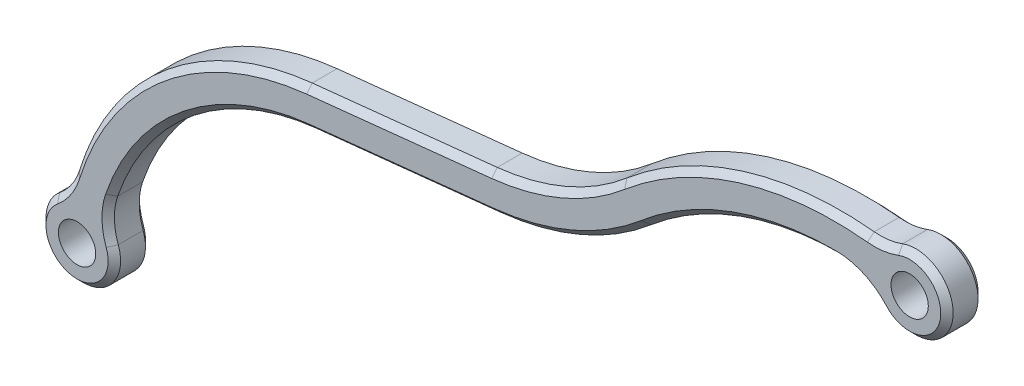
SolidWorks part; units mm, degrees
ref_plane "Спереди" through (0, 0, 0) normal (0, 0, 1) x (1, 0, 0)
ref_plane "Сверху" through (0, 0, 0) normal (0, 1, 0) x (1, 0, 0)
ref_plane "Справа" through (0, 0, 0) normal (1, 0, 0) x (0, 0, -1)
other "Configuration Table"
sketch "Sketch1" plane through (0, 0, 0) normal (0, 0, 1) x (1, 0, 0)
  line L0 (-54.4883, 1.7083) -> (-63.9363, 0.7152) construction
  line L1 (-54.4883, 1.7083) -> (-63.9363, 0.7152) construction
  line L2 (-65.383, -1.297) -> (-50.4992, 0.2674)
  circle A0 centre (-83.9505, -19.9121) radius 1.5 construction
  circle A1 centre (-83.9505, -19.9121) radius 1.5
  circle A2 centre (-17, 9.9282) radius 1.5 construction
  circle A3 centre (-17, 9.9282) radius 1.5
  circle A4 centre (-83.9505, -19.9121) radius 3
  circle A5 centre (-17, 9.9282) radius 3
  arc A6 (-12.8452, 4.492) -> (-12.8452, 1.508) centre (-13, 3) ccw construction
  arc A7 (-12.8452, 4.492) -> (-12.8452, 1.508) centre (-13, 3) ccw construction
  arc A9 (-83.3396, -17.8158) -> (-65.383, -1.297) centre (-63.2448, -21.6405) cw
  arc A10 (-50.4992, 0.2674) -> (-39.2623, 5.0886) centre (-52.6577, 20.804) ccw
  arc A11 (-39.2623, 5.0886) -> (-19.139, 10.7644) centre (-23.0284, -13.9569) cw
  dimension "D1" = 6
  dimension "D2" = 6
extrude "Boss-Extrude1" add sketch "Sketch1" along normal blind 3
sketch "Sketch2" plane through (0, 0, 0) normal (0, 0, 1) x (1, 0, 0)
  line L0 (-65.383, -1.297) -> (-50.4992, 0.2674) construction
  line L1 (-65.383, -1.297) -> (-50.4992, 0.2674)
  arc A0 (-19.139, 10.7644) -> (-39.2623, 5.0886) centre (-23.0284, -13.9569) ccw construction
  arc A1 (-50.4992, 0.2674) -> (-39.2623, 5.0886) centre (-52.6577, 20.804) ccw construction
  arc A2 (-65.383, -1.297) -> (-83.3396, -17.8158) centre (-63.2448, -21.6405) ccw construction
  arc A3 (-18.8959, 10.7249) -> (-39.2623, 5.0886) centre (-23.0284, -13.9569) ccw
  arc A4 (-50.4992, 0.2674) -> (-39.2623, 5.0886) centre (-52.6577, 20.804) ccw
  arc A5 (-65.383, -1.297) -> (-83.3396, -17.8158) centre (-63.2448, -21.6405) ccw
extrude "Extrude-Thin1" add sketch "Sketch2" along normal blind 3 thin thin type mid plane wall 3
fillet "Fillet1" radius 5 4 edges at (-84.7063, -17.0089, 1.5) (-81.8095, -17.8108, 1.5) (-19.9468, 9.3658, 1.5) (-18.9047, 12.246, 1.5)
chamfer "Chamfer1" distance 0.5 angle 45 28 edges at (-31.1067, 8.138, 0) (-31.1067, 8.138, 3) (-20.8969, 9.1322, 0) (-43.9243, 0.4487, 0) (-43.9243, 0.4487, 3) (-14.0837, 9.2244, 0) (-57.7843, -2.0066, 0) (-57.7843, -2.0066, 3) (-19.1882, 12.4496, 0) (-75.0623, -6.8195, 3) (-75.0623, -6.8195, 0) (-30.9252, 11.3657, 3) (-30.9252, 11.3657, 0) (-81.4502, -17.1934, 0) (-45.1071, 3.2057, 0) (-45.1071, 3.2057, 3) (-84.7375, -22.8071, 0) (-58.0979, 0.977, 0) (-58.0979, 0.977, 3) (-84.8606, -16.5059, 0) (-77.1954, -4.6867, 0) (-77.1954, -4.6867, 3) (-20.8969, 9.1322, 3) (-14.0837, 9.2244, 3) (-19.1882, 12.4496, 3) (-81.4502, -17.1934, 3) (-84.7375, -22.8071, 3) (-84.8606, -16.5059, 3)
